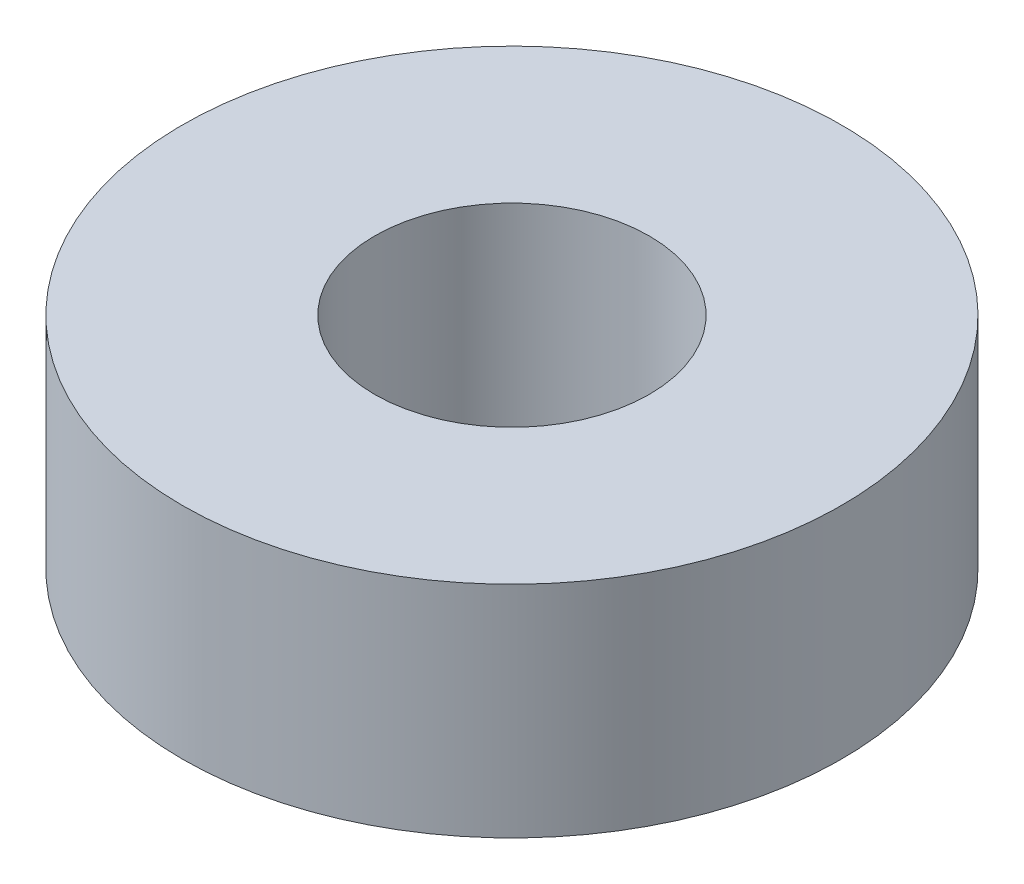
SolidWorks part; units mm, degrees
ref_plane "Front Plane" through (0, 0, 0) normal (0, 0, 1) x (1, 0, 0)
ref_plane "Top Plane" through (0, 0, 0) normal (0, 1, 0) x (1, 0, 0)
ref_plane "Right Plane" through (0, 0, 0) normal (1, 0, 0) x (0, 0, -1)
sketch "Sketch1" plane through (0, 0, 0) normal (0, 1, 0) x (1, 0, 0)
  circle A0 centre (0, 0) radius 1.9844
  circle A1 centre (0, 0) radius 4.7625
  dimension "D1" = 3.9688
  dimension "D2" = 9.525
extrude "Boss-Extrude1" add sketch "Sketch1" along normal blind 3.175
